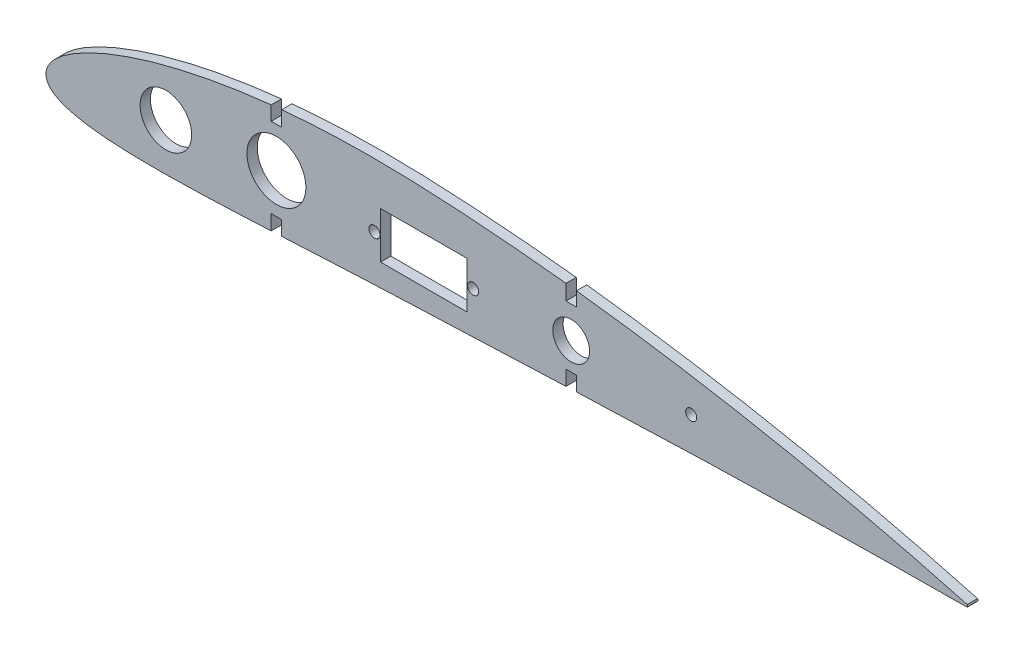
SolidWorks part; units mm, degrees
material "Фанера"
ref_plane "Front Plane" through (0, 0, 0) normal (0, 0, 1) x (1, 0, 0)
ref_plane "Top Plane" through (0, 0, 0) normal (0, 1, 0) x (1, 0, 0)
ref_plane "Right Plane" through (0, 0, 0) normal (1, 0, 0) x (0, 0, -1)
curve "Кривая5"
  spline degree 3 poles (0.048, 0.6214, 0) (0.0227, 0.3735, 0) (-0.0278, -0.1225, 0) (0.078, -0.8844, 0) (0.3497, -1.6388, 0) (0.8143, -2.3651, 0) (1.4635, -3.0393, 0) (2.291, -3.661, 0) (3.3059, -4.2358, 0) (4.5353, -4.7737, 0) (6.0297, -5.2822, 0) (7.869, -5.7653, 0) (10.1688, -6.2217, 0) (13.0754, -6.6396, 0) (16.7281, -6.993, 0) (21.19, -7.2473, 0) (26.4, -7.3766, 0) (32.1974, -7.3763, 0) (38.3978, -7.2614, 0) (44.8576, -7.0566, 0) (51.4865, -6.7865, 0) (58.231, -6.4723, 0) (65.0521, -6.1329, 0) (71.9108, -5.784, 0) (78.7714, -5.4397, 0) (85.6105, -5.111, 0) (92.4321, -4.805, 0) (99.255, -4.532, 0) (106.0974, -4.2783, 0) (112.9692, -4.0031, 0) (119.8644, -3.7232, 0) (126.7739, -3.4401, 0) (133.6816, -3.1587, 0) (140.5819, -2.8824, 0) (147.472, -2.6139, 0) (154.3526, -2.3556, 0) (161.225, -2.1094, 0) (168.0909, -1.8766, 0) (174.9516, -1.6586, 0) (181.8086, -1.4564, 0) (188.6632, -1.2704, 0) (195.5166, -1.1011, 0) (202.3695, -0.9486, 0) (209.2212, -0.8129, 0) (216.0668, -0.6936, 0) (222.8864, -0.5903, 0) (229.6176, -0.5029, 0) (236.0874, -0.4315, 0) (241.9808, -0.3765, 0) (246.559, -0.3395, 0) (249.1205, -0.3213, 0) (250, -0.315, 0) knots 0 0 0 0 0.002941 0.005884 0.009016 0.012365 0.016008 0.020037 0.024574 0.029784 0.035897 0.04324 0.052276 0.063635 0.077983 0.095698 0.11652 0.139661 0.164312 0.189919 0.216157 0.242838 0.269834 0.296993 0.324123 0.351139 0.378036 0.404946 0.431961 0.459078 0.486347 0.513641 0.540929 0.568176 0.59538 0.622543 0.649673 0.676775 0.703855 0.730919 0.757971 0.785018 0.812062 0.839103 0.866132 0.893099 0.919831 0.94581 0.969681 0.98959 1 1 1 1
curve "Кривая6"
  spline degree 3 poles (250, 0.315, 0) (249.1557, 0.545, 0) (246.7202, 1.2085, 0) (242.3913, 2.3583, 0) (236.8498, 3.7876, 0) (230.7799, 5.298, 0) (224.4559, 6.8129, 0) (218.0305, 8.2916, 0) (211.5624, 9.7197, 0) (205.0724, 11.0924, 0) (198.568, 12.4079, 0) (192.0524, 13.6653, 0) (185.5276, 14.8641, 0) (178.9953, 16.0034, 0) (172.4571, 17.0824, 0) (165.9143, 18.0998, 0) (159.3687, 19.0545, 0) (152.8218, 19.9449, 0) (146.2754, 20.7693, 0) (139.7314, 21.5257, 0) (133.1918, 22.212, 0) (126.6587, 22.8257, 0) (120.1368, 23.364, 0) (113.6286, 23.8247, 0) (107.1527, 24.2002, 0) (100.7411, 24.4984, 0) (94.4118, 24.6866, 0) (88.1559, 24.7401, 0) (81.949, 24.6588, 0) (75.7805, 24.441, 0) (69.6537, 24.0819, 0) (63.5754, 23.578, 0) (57.5552, 22.9249, 0) (51.6058, 22.1191, 0) (45.7444, 21.1566, 0) (39.9959, 20.0354, 0) (34.3979, 18.7563, 0) (29.0104, 17.3276, 0) (23.9258, 15.7719, 0) (19.2707, 14.1343, 0) (15.1791, 12.4833, 0) (11.7405, 10.8956, 0) (8.9594, 9.4296, 0) (6.7609, 8.1086, 0) (5.0337, 6.9246, 0) (3.6717, 5.8542, 0) (2.5921, 4.8713, 0) (1.7382, 3.9526, 0) (1.0699, 3.0809, 0) (0.5716, 2.2416, 0) (0.2158, 1.4308, 0) (0.1023, 0.8832, 0) (0.048, 0.6214, 0) knots 0 0 0 0 0.010162 0.029313 0.052012 0.076619 0.101948 0.127526 0.153184 0.178868 0.204558 0.230246 0.255926 0.281594 0.307246 0.332878 0.358485 0.384061 0.409603 0.435104 0.460559 0.485959 0.511303 0.536552 0.561723 0.586629 0.611085 0.635251 0.659272 0.683164 0.706922 0.730536 0.753983 0.777235 0.800246 0.822951 0.845237 0.866916 0.887662 0.906968 0.924203 0.938879 0.950932 0.960693 0.968647 0.975233 0.980795 0.985584 0.989782 0.993521 0.996902 1 1 1 1
sketch "Эскиз1" plane through (0, 0, 0) normal (0, 0, 1) x (1, 0, 0)
  line L0 (250.1305, 0) -> (250.1305, 54.8427) construction
  line L1 (0, 0) -> (0, 70.5199) construction
  line L2 (0, 0) -> (253.0634, 0) construction
  line L3 (62.5326, 62.6361) -> (62.5326, -41.5636) construction
  line L4 (142.5326, 67.9319) -> (142.5326, 25.1988) construction
  line L5 (175.0913, 63.8571) -> (175.0913, -32.3947) construction
  line L6 (32.5326, -14.3434) -> (32.5326, 29.5903) construction
  line L7 (142.5326, 21.1988) -> (142.5326, -57.0034) construction
  line L8 (61.1076, 19.4501) -> (63.9576, 19.4501)
  line L9 (61.1076, 19.4501) -> (61.1076, 23.3031)
  line L11 (63.9576, 19.4501) -> (63.9576, 23.5885)
  line L12 (61.1076, 19.4501) -> (62.5326, 23.4501) construction
  line L13 (62.5326, 23.4501) -> (63.9576, 19.4501) construction
  line L15 (61.1076, -6.3284) -> (61.1076, -2.2577)
  line L16 (61.1076, -2.2577) -> (63.9576, -2.2577)
  line L17 (63.9576, -6.1866) -> (63.9576, -2.2577)
  line L18 (62.5326, -6.2577) -> (63.9576, -2.2577) construction
  line L19 (61.1076, -2.2577) -> (62.5326, -6.2577) construction
  line L20 (141.1076, 17.1988) -> (143.9576, 17.1988)
  line L21 (141.1076, 17.1988) -> (141.1076, 21.3608)
  line L23 (143.9576, 17.1988) -> (143.9576, 21.0336)
  line L24 (141.1076, 17.1988) -> (142.5326, 21.1988) construction
  line L25 (142.5326, 21.1988) -> (143.9576, 17.1988) construction
  line L26 (114.2826, 13.7939) -> (117.5526, 13.7939) construction
  line L28 (141.1076, -2.8629) -> (141.1076, 1.1931)
  line L29 (141.1076, 1.1931) -> (143.9576, 1.1931)
  line L30 (143.9576, -2.7512) -> (143.9576, 1.1931)
  line L31 (142.5326, -2.8069) -> (143.9576, 1.1931) construction
  line L32 (141.1076, 1.1931) -> (142.5326, -2.8069) construction
  line L33 (90.7826, 1.1939) -> (114.2826, 1.1939)
  line L34 (90.7826, 1.1939) -> (90.7826, 13.7939)
  line L35 (90.7826, 13.7939) -> (114.2826, 13.7939)
  line L36 (114.2826, 1.1939) -> (114.2826, 13.7939)
  line L37 (90.7826, 1.1939) -> (114.2826, 13.7939) construction
  line L38 (90.7826, 13.7939) -> (114.2826, 1.1939) construction
  line L39 (117.5526, 13.7939) -> (117.5526, 1.1939) construction
  line L40 (117.5526, 1.1939) -> (114.2826, 1.1939) construction
  line L41 (102.5326, 20.3562) -> (102.5326, -2.2577) construction
  line L42 (87.5126, 1.1939) -> (90.7826, 1.1939) construction
  line L43 (90.7826, 13.7939) -> (87.5126, 13.7939) construction
  line L44 (87.5126, 13.7939) -> (87.5126, 1.1939) construction
  arc A0 (250, 0.315) -> (250, -0.315) centre (249.685, 0) cw
  circle A1 centre (62.5326, 8.5962) radius 8
  circle A2 centre (142.5326, 8.5962) radius 5
  circle A3 centre (32.5326, 5.4481) radius 7
  circle A6 centre (175.0913, 7.4939) radius 1.5
  arc A7 (175.0913, 16.6448) -> (175.0913, -1.657) centre (175.0913, 7.4939) ccw
  circle A8 centre (115.9176, 7.4939) radius 1.5
  circle A9 centre (89.1476, 7.4939) radius 1.5
  spline S2 degree 3 poles (0.048, 0.6214) (0.0227, 0.3735) (-0.0278, -0.1225) (0.078, -0.8844) (0.3497, -1.6388) (0.8143, -2.3651) (1.4635, -3.0393) (2.291, -3.661) (3.3059, -4.2358) (4.5353, -4.7737) (6.0297, -5.2822) (7.869, -5.7653) (10.1688, -6.2217) (13.0754, -6.6396) (16.7281, -6.993) (21.19, -7.2473) (26.4, -7.3766) (32.1974, -7.3763) (38.3978, -7.2614) (44.8576, -7.0566) (51.4865, -6.7865) (56.9206, -6.5334) (60.1398, -6.3761) (61.1076, -6.3284) knots 0 0 0 0 0.002941 0.005884 0.009016 0.012365 0.016008 0.020037 0.024574 0.029784 0.035897 0.04324 0.052276 0.063635 0.077983 0.095698 0.11652 0.139661 0.164312 0.189919 0.216157 0.242838 0.254307 0.254307 0.254307 0.254307
  spline S3 degree 3 poles (250, 0.315) (249.1557, 0.545) (246.7202, 1.2085) (242.3913, 2.3583) (236.8498, 3.7876) (230.7799, 5.298) (224.4559, 6.8129) (218.0305, 8.2916) (211.5624, 9.7197) (205.0724, 11.0924) (198.568, 12.4079) (192.0524, 13.6653) (185.5276, 14.8641) (178.9953, 16.0034) (172.4571, 17.0824) (165.9143, 18.0998) (159.3687, 19.0545) (152.8218, 19.9449) (147.6839, 20.5919) (144.7288, 20.9433) (143.9576, 21.0336) knots 0 0 0 0 0.010162 0.029313 0.052012 0.076619 0.101948 0.127526 0.153184 0.178868 0.204558 0.230246 0.255926 0.281594 0.307246 0.332878 0.358485 0.384061 0.409603 0.418619 0.418619 0.418619 0.418619
  spline S4 degree 3 poles (61.1076, 23.3031) (59.9179, 23.1768) (56.7397, 22.8145) (51.6058, 22.1191) (45.7444, 21.1566) (39.9959, 20.0354) (34.3979, 18.7563) (29.0104, 17.3276) (23.9258, 15.7719) (19.2707, 14.1343) (15.1791, 12.4833) (11.7405, 10.8956) (8.9594, 9.4296) (6.7609, 8.1086) (5.0337, 6.9246) (3.6717, 5.8542) (2.5921, 4.8713) (1.7382, 3.9526) (1.0699, 3.0809) (0.5716, 2.2416) (0.2158, 1.4308) (0.1023, 0.8832) (0.048, 0.6214) knots 0.740091 0.740091 0.740091 0.740091 0.753983 0.777235 0.800246 0.822951 0.845237 0.866916 0.887662 0.906968 0.924203 0.938879 0.950932 0.960693 0.968647 0.975233 0.980795 0.985584 0.989782 0.993521 0.996902 1 1 1 1
  spline S5 degree 3 poles (63.9576, -6.1866) (64.3178, -6.1685) (66.9697, -6.0353) (71.9108, -5.784) (78.7714, -5.4397) (85.6105, -5.111) (92.4321, -4.805) (99.255, -4.532) (106.0974, -4.2783) (112.9692, -4.0031) (119.8644, -3.7232) (126.7739, -3.4401) (133.8556, -3.1516) (138.6334, -2.9604) (141.1076, -2.8629) knots 0.265565 0.265565 0.265565 0.265565 0.269834 0.296993 0.324123 0.351139 0.378036 0.404946 0.431961 0.459078 0.486347 0.513641 0.540929 0.570237 0.570237 0.570237 0.570237
  spline S6 degree 3 poles (143.9576, -2.7512) (145.1302, -2.7056) (148.5961, -2.5717) (154.3526, -2.3556) (161.225, -2.1094) (168.0909, -1.8766) (174.9516, -1.6586) (181.8086, -1.4564) (188.6632, -1.2704) (195.5166, -1.1011) (202.3695, -0.9486) (211.4992, -0.7677) (220.6031, -0.6199) (229.6176, -0.5029) (236.0874, -0.4315) (241.9808, -0.3765) (246.559, -0.3395) (249.1205, -0.3213) (250, -0.315) knots 0.58149 0.58149 0.58149 0.58149 0.59538 0.622543 0.649673 0.676775 0.703855 0.730919 0.757971 0.785018 0.812062 0.839103 0.893099 0.919831 0.94581 0.969681 0.98959 1 1 1 1
  spline S7 degree 3 poles (141.1076, 21.3608) (140.6472, 21.4126) (138.0081, 21.7065) (133.1918, 22.212) (126.6587, 22.8257) (120.1368, 23.364) (113.6286, 23.8247) (107.1527, 24.2002) (100.7411, 24.4984) (94.4118, 24.6866) (88.1559, 24.7401) (81.949, 24.6588) (75.7805, 24.441) (69.7854, 24.0896) (65.8508, 23.7665) (63.9576, 23.5885) knots 0.429724 0.429724 0.429724 0.429724 0.435104 0.460559 0.485959 0.511303 0.536552 0.561723 0.586629 0.611085 0.635251 0.659272 0.683164 0.706922 0.729004 0.729004 0.729004 0.729004
  point P20 (102.5326, 7.4939)
  point P22 (62.5326, 23.4501)
  point P23 (62.5326, -6.2577)
  point P26 (32.5326, 18.2506)
  point P27 (32.5326, -7.3543)
  point P30 (62.5326, 23.4501)
  point P31 (62.5326, -6.2577)
  point P40 (142.5326, 21.1988)
  point P43 (142.5326, -2.8069)
  point P53 (175.0913, 16.6448)
  point P56 (175.0913, -1.657)
  point P74 (0, 0)
  point P75 (115.9176, 13.7939)
  dimension "D3" = 16
  dimension "D8" = 14
  dimension "D10" = 10
  dimension "D27" = 3
  dimension "D30" = 3
  dimension "D1" = 250.1305
  dimension "D2" = 62.5326
  dimension "D4" = 80
  dimension "D5" = 75.0391
  dimension "D6" = 29.7079
  dimension "D7" = 14.8539
  dimension "D12" = 30
  dimension "D13" = 25.6049
  dimension "D14" = 12.8025
  dimension "D15" = 2.85
  dimension "D16" = 4
  dimension "D17" = 1.425
  dimension "D18" = 2.85
  dimension "D19" = 4
  dimension "D20" = 1.425
  dimension "D21" = 2.85
  dimension "D22" = 4
  dimension "D23" = 1.425
  dimension "D24" = 2.85
  dimension "D25" = 4
  dimension "D26" = 1.425
  dimension "D9" = 12.6
  dimension "D11" = 23.5
  dimension "D28" = 40
  dimension "D29" = 3.27
extrude "Бобышка-Вытянуть1" add sketch "Эскиз1" along normal mid plane 2.8 contours L21 S7 L11 L8 L9 S4 S2 L15 L16 L17 S5 L28 L29 L30 S6 A7 S3 L23 L20 A1 A2 A3 L34 | A7 S6 A0 S3 A6
equation "\"D2@Эскиз1\"=\"D1@Эскиз1\"/4"
equation "\"D7@Эскиз1\"=\"D6@Эскиз1\"/2"
equation "\"D5@Эскиз1\"=\"D1@Эскиз1\"*0.3"
equation "\"D14@Эскиз1\"=\"D13@Эскиз1\"/2"
equation "\"t\"= 2.85"
equation "\"D17@Эскиз1\"=\"D15@Эскиз1\"/2"
equation "\"D18@Эскиз1\"=\"t\""
equation "\"D20@Эскиз1\"=\"D18@Эскиз1\"/2"
equation "\"D21@Эскиз1\"=\"t\""
equation "\"D23@Эскиз1\"=\"D21@Эскиз1\"/2"
equation "\"D24@Эскиз1\"=\"t\""
equation "\"D26@Эскиз1\"=\"D24@Эскиз1\"/2"
